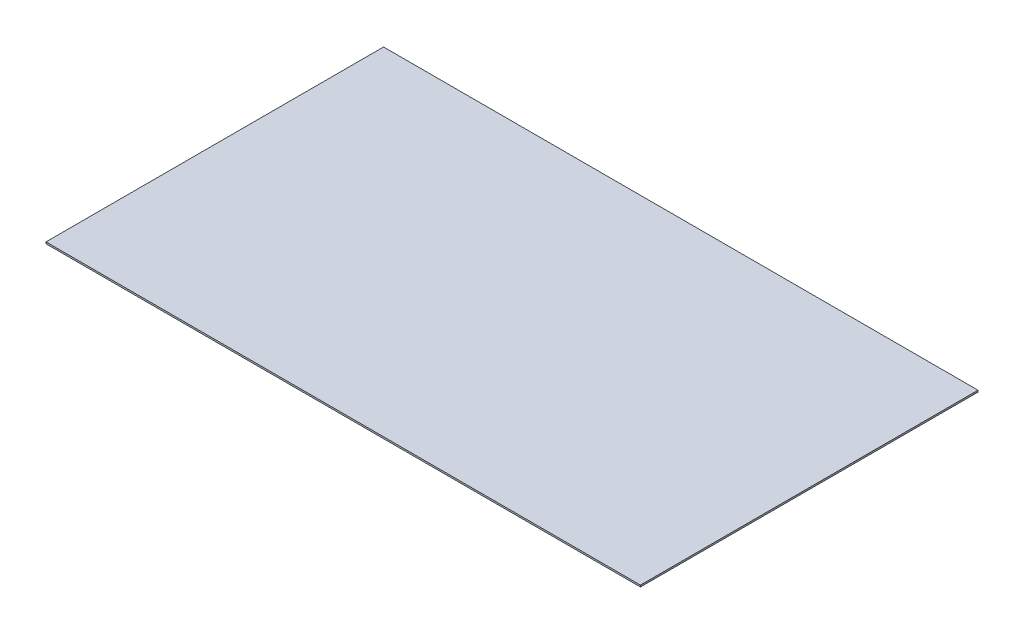
SolidWorks part; units mm, degrees
ref_plane "Front Plane" through (0, 0, 0) normal (0, 0, 1) x (1, 0, 0)
ref_plane "Top Plane" through (0, 0, 0) normal (0, 1, 0) x (1, 0, 0)
ref_plane "Right Plane" through (0, 0, 0) normal (1, 0, 0) x (0, 0, -1)
sketch "Sketch1" plane through (0, 0, 0) normal (0, 1, 0) x (1, 0, 0)
  line L1 (281.15, -159.65) -> (-281.15, -159.65)
  line L2 (281.15, -159.65) -> (281.15, 159.65)
  line L3 (281.15, 159.65) -> (-281.15, 159.65)
  line L4 (-281.15, -159.65) -> (-281.15, 159.65)
  line L5 (281.15, -159.65) -> (-281.15, 159.65) construction
  line L6 (281.15, 159.65) -> (-281.15, -159.65) construction
  point P0 (0, 0)
  dimension "D1" = 319.3
  dimension "D2" = 562.3
extrude "Boss-Extrude1" add sketch "Sketch1" along normal blind 1.5875
